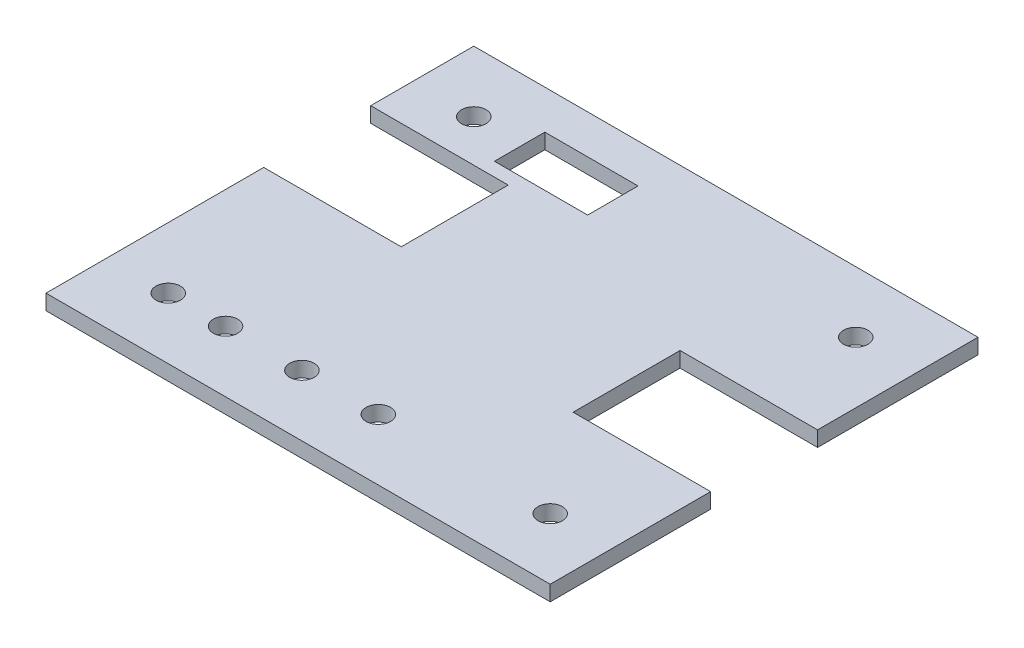
SolidWorks part; units mm, degrees
ref_plane "前视基准面" through (0, 0, 0) normal (0, 0, 1) x (1, 0, 0)
ref_plane "上视基准面" through (0, 0, 0) normal (0, 1, 0) x (1, 0, 0)
ref_plane "右视基准面" through (0, 0, 0) normal (1, 0, 0) x (0, 0, -1)
sketch "草图1" plane through (0, 0, 0) normal (0, 1, 0) x (1, 0, 0)
  line L1 (33, -28) -> (-33, -28)
  line L2 (33, -28) -> (33, 28)
  line L3 (33, 28) -> (-33, 28)
  line L4 (-33, -28) -> (-33, 28)
  line L5 (33, -28) -> (-33, 28) construction
  line L6 (33, 28) -> (-33, -28) construction
  point P0 (0, 0)
  dimension "D1" = 66
  dimension "D2" = 56
extrude "凸台-拉伸1" add sketch "草图1" along normal blind 2
sketch "草图2" plane through (0, 2, 0) normal (0, 1, 0) x (1, 0, 0)
  line L1 (25, -20) -> (-25, -20) construction
  line L2 (25, -20) -> (25, 20) construction
  line L3 (25, 20) -> (-25, 20) construction
  line L4 (-25, -20) -> (-25, 20) construction
  line L5 (25, -20) -> (-25, 20) construction
  line L6 (25, 20) -> (-25, -20) construction
  circle A0 centre (-25, 20) radius 1.6
  point P0 (0, 0)
  dimension "D3" = 3.2
  dimension "D1" = 50
  dimension "D2" = 40
extrude "切除-拉伸1" cut sketch "草图2" against normal blind 2
pattern_linear "阵列(线性)1" count 2 spacing 50 along (1, 0, 0) count 2 spacing 40 along (0, 0, 1) of "切除-拉伸1"
sketch "草图4" plane through (0, 0, 0) normal (0, -1, 0) x (1, 0, 0)
  circle A0 centre (-17.5, 20.0001) radius 1.6
  circle A1 centre (-7.5, 20.0001) radius 1.6
  circle A2 centre (2.4999, 19.9997) radius 1.6
  dimension "D1" = 3.2
  dimension "D2" = 3.2
  dimension "D3" = 3.2
extrude "切除-拉伸2" cut sketch "草图4" against normal blind 2
sketch "草图5" plane through (0, 0, 0) normal (0, -1, 0) x (1, 0, 0)
  line L0 (33, 7) -> (33, -7)
  line L1 (33, 7) -> (15, 7)
  line L2 (33, -7) -> (15, -7)
  line L3 (15, 7) -> (15, -7)
  dimension "D1" = 18
extrude "切除-拉伸3" cut sketch "草图5" against normal blind 2
sketch "草图7" plane through (0, 0, 0) normal (0, -1, 0) x (1, 0, 0)
  line L0 (-33, -0.5) -> (-33, -14.5)
  line L1 (-33, -0.5) -> (-15, -0.5)
  line L2 (-33, -14.5) -> (-15, -14.5)
  line L3 (-15, -0.5) -> (-15, -14.5)
  dimension "D1" = 18
extrude "切除-拉伸4" cut sketch "草图7" against normal blind 2
sketch "草图8" plane through (0, 2, 0) normal (0, 1, 0) x (1, 0, 0)
  line L0 (-18.6, 22.9) -> (-18.6, 16.3)
  line L1 (-18, 22.3) -> (-7, 22.3) construction
  line L2 (-18, 22.3) -> (-18, 16.9) construction
  line L3 (-18, 16.9) -> (-7, 16.9) construction
  line L4 (-7, 22.3) -> (-7, 16.9) construction
  line L5 (-18.6, 16.3) -> (-6.4, 16.3)
  line L6 (-6.4, 22.9) -> (-6.4, 16.3)
  line L7 (-18.6, 22.9) -> (-6.4, 22.9)
  dimension "D1" = 0.6
extrude "切除-拉伸5" cut sketch "草图8" against normal blind 2
